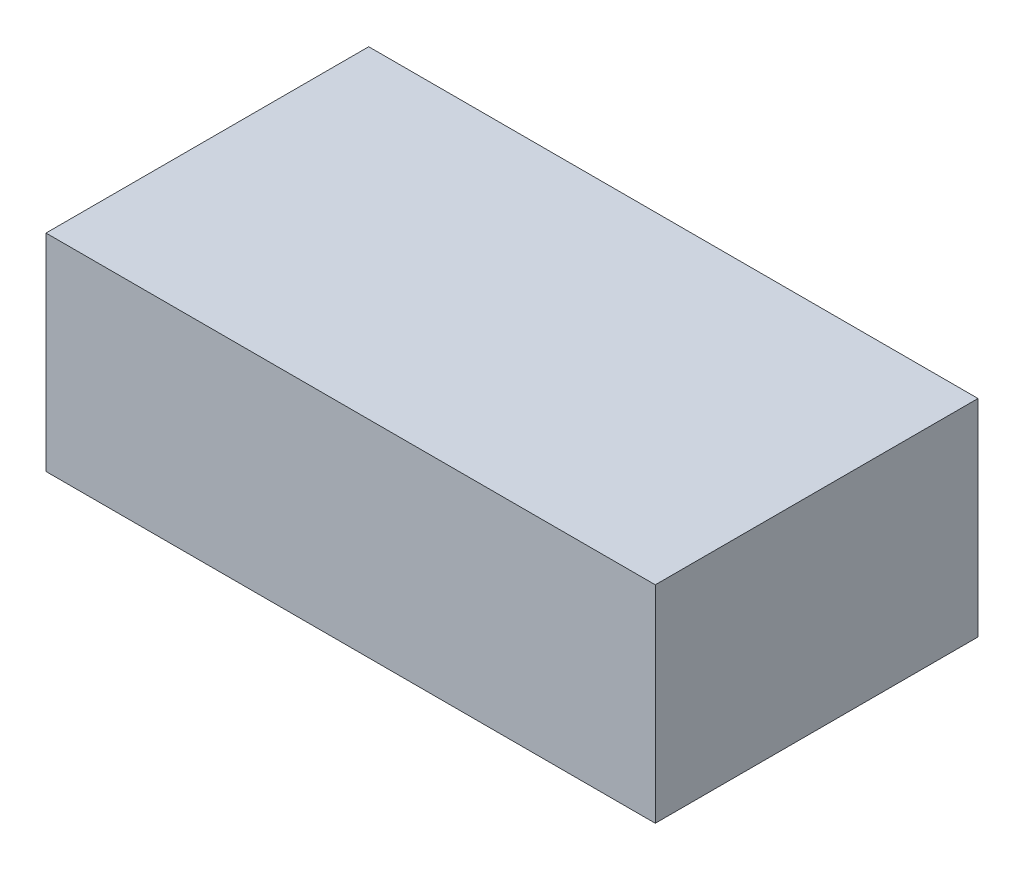
SolidWorks part; units mm, degrees
ref_plane "Front Plane" through (0, 0, 0) normal (0, 0, 1) x (1, 0, 0)
ref_plane "Top Plane" through (0, 0, 0) normal (0, 1, 0) x (1, 0, 0)
ref_plane "Right Plane" through (0, 0, 0) normal (1, 0, 0) x (0, 0, -1)
sketch "Sketch1" plane through (0, 0, 0) normal (0, 1, 0) x (1, 0, 0)
  line L1 (-1.4986, 0.7938) -> (1.4986, 0.7938)
  line L2 (-1.4986, 0.7938) -> (-1.4986, -0.7938)
  line L3 (-1.4986, -0.7938) -> (1.4986, -0.7938)
  line L4 (1.4986, 0.7938) -> (1.4986, -0.7938)
  point P4 (0, 0.7938)
  point P5 (1.4986, 0)
  dimension "D1" = 1.5875
  dimension "D2" = 2.9972
extrude "Boss-Extrude1" add sketch "Sketch1" along normal blind 1.016
